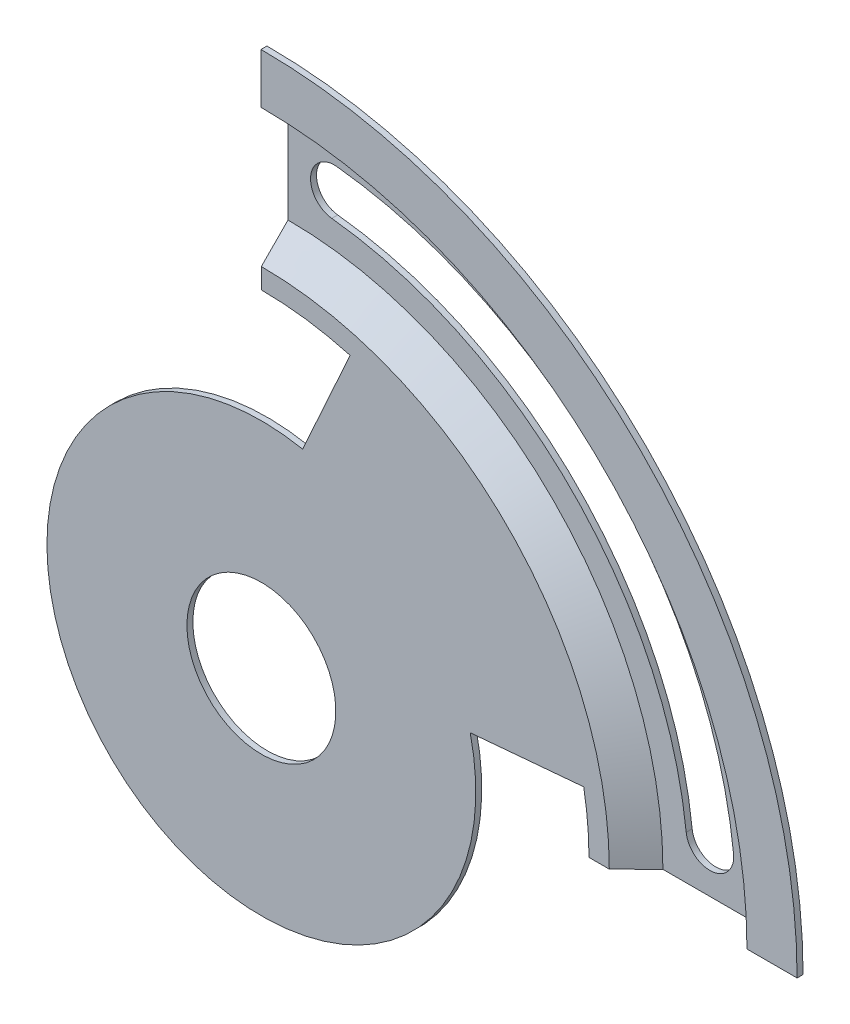
SolidWorks part; units mm, degrees
material "Galvanized Steel"
ref_plane "Front Plane" through (0, 0, 0) normal (0, 0, 1) x (1, 0, 0)
ref_plane "Top Plane" through (0, 0, 0) normal (0, 1, 0) x (1, 0, 0)
ref_plane "Right Plane" through (0, 0, 0) normal (1, 0, 0) x (0, 0, -1)
sketch "Sketch1" plane through (0, 0, 0) normal (0, 1, 0) x (1, 0, 0)
  line L0 (15.7283, -17.7674) -> (7.7283, -17.7674)
  line L1 (7.7283, -17.7674) -> (3.2585, -13.2372)
  line L2 (3.2585, -13.2372) -> (-11.7415, -13.2372)
  line L3 (-11.7415, -13.2372) -> (-16.2716, -17.707)
  line L4 (-16.2716, -17.707) -> (-19.2716, -17.707)
  line L5 (-74.2717, -17.707) -> (-74.2717, -49.8443)
  line L6 (15.7283, -18.7674) -> (7.3102, -18.7674)
  line L7 (7.3102, -18.7674) -> (2.8404, -14.2372)
  line L8 (2.8404, -14.2372) -> (-11.3312, -14.2372)
  line L9 (-11.3312, -14.2372) -> (-15.8613, -18.707)
  line L10 (-15.8613, -18.707) -> (-19.2716, -18.707)
  line L11 (15.7283, -17.7674) -> (15.7283, -18.7674)
  line L12 (-19.2716, -17.707) -> (-19.2716, -18.707)
  dimension "D1" = 35
  dimension "D2" = 15
  dimension "D3" = 3
  dimension "D4" = 8
  dimension "D5" = 90
  dimension "D6" = 1
revolve "Revolve1" add sketch "Sketch1" angle 90 about L5
sketch "Sketch2" plane through (0, 0, 17.707) normal (0, 0, -1) x (-1, 0, 0)
  line L0 (67.343, 35.3269) -> (59.3717, 52.9433)
  line L2 (39.2081, 8.1576) -> (20.156, 9.8231)
  circle A0 centre (74.2717, 0) radius 12.5
  arc A1 (39.2081, 8.1576) -> (67.343, 35.3269) centre (74.2717, 0) ccw
  arc A2 (74.2717, 55.0001) -> (19.2716, 0) centre (74.2717, 0) ccw construction
  arc A3 (59.3717, 52.9433) -> (20.156, 9.8231) centre (74.2717, 0) ccw
  dimension "D1" = 25
  dimension "D2" = 72
extrude "Boss-Extrude1" add sketch "Sketch2" against normal blind 1
sketch "Sketch3" plane through (0, 0, 13.2372) normal (0, 0, -1) x (-1, 0, 0)
  line L1 (74.2717, 0) -> (33.2594, 41.0122)
  arc A0 (66.2155, 74.8209) -> (-0.5492, 8.0562) centre (74.2717, 0) ccw
  arc A1 (66.9213, 66.8505) -> (7.4212, 7.3503) centre (74.2717, 0) ccw
  arc A2 (66.9213, 66.8505) -> (66.2155, 74.8209) centre (66.4839, 70.8282) ccw
  arc A3 (74.2717, 58.0001) -> (16.2716, 0) centre (74.2717, 0) ccw construction
  arc A4 (7.4212, 7.3503) -> (-0.5492, 8.0562) centre (3.4435, 7.7877) cw
  circle A5 centre (74.2717, 0) radius 67.2534 construction
  circle A6 centre (74.2717, 0) radius 75.2534 construction
  dimension "D1" = 8
extrude "Cut-Extrude1" cut sketch "Sketch3" against normal through all both and the other way through all contours A4 A1 A2 A0
